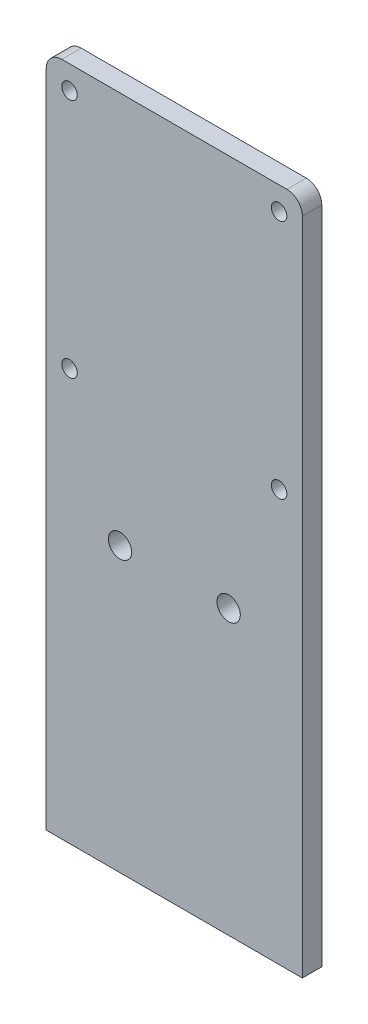
SolidWorks part; units mm, degrees
ref_plane "Front Plane" through (0, 0, 0) normal (0, 0, 1) x (1, 0, 0)
ref_plane "Top Plane" through (0, 0, 0) normal (0, 1, 0) x (1, 0, 0)
ref_plane "Right Plane" through (0, 0, 0) normal (1, 0, 0) x (0, 0, -1)
sketch "Sketch1" plane through (0, 0, 0) normal (0, 0, 1) x (1, 0, 0)
  line L0 (0, 50) -> (16.5, 87) construction
  line L1 (0, 0) -> (33, 0)
  line L2 (0, 0) -> (0, 85)
  line L3 (2, 87) -> (31, 87)
  line L4 (16.5, 0) -> (16.5, 87) construction
  line L5 (8.25, 68.5) -> (0, 68.5) construction
  line L6 (0, 40) -> (33, 40) construction
  line L7 (24.75, 68.5) -> (33, 68.5) construction
  line L8 (33, 50) -> (16.5, 87) construction
  line L9 (33, 0) -> (33, 85)
  circle A0 centre (3, 84) radius 1
  circle A1 centre (3, 53) radius 1
  circle A2 centre (9.5, 36.5) radius 1.5
  arc A3 (0, 85) -> (2, 87) centre (2, 85) cw
  arc A4 (33, 85) -> (31, 87) centre (31, 85) ccw
  circle A5 centre (23.5, 36.5) radius 1.5
  circle A6 centre (30, 53) radius 1
  circle A7 centre (30, 84) radius 1
  point P5 (0, 40)
  point P6 (0, 50)
  point P16 (16.5, 38)
  point P19 (13.1424, 36.5)
  point P23 (16.5, 40)
  point P36 (33, 50)
  point P37 (33, 40)
  dimension "D5" = 2
  dimension "D6" = 2
  dimension "D7" = 2
  dimension "D8" = 3
  dimension "D10" = 5.5
  dimension "D4" = 2
  dimension "D1" = 87
  dimension "D2" = 16.5
  dimension "D3" = 40
  dimension "D9" = 2
extrude "Boss-Extrude1" add sketch "Sketch1" along normal blind 2.5
